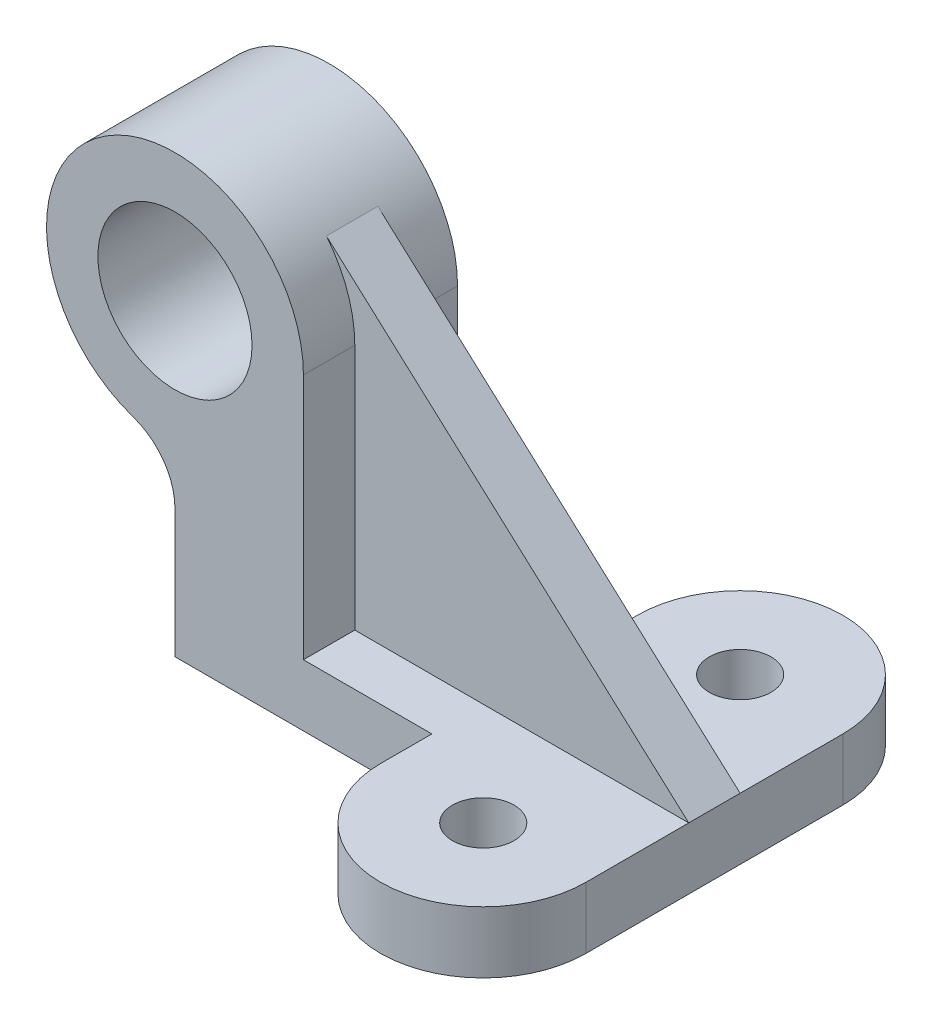
SolidWorks part; units mm, degrees
ref_plane "Front Plane" through (0, 0, 0) normal (0, 0, 1) x (1, 0, 0)
ref_plane "Top Plane" through (0, 0, 0) normal (0, 1, 0) x (1, 0, 0)
ref_plane "Right Plane" through (0, 0, 0) normal (1, 0, 0) x (0, 0, -1)
sketch "Sketch2" plane through (0, 0, 0) normal (0, 1, 0) x (1, 0, 0)
  line L0 (0, 150.8422) -> (0, -117.9442) construction
  line L1 (-243.4091, 0) -> (231.4014, 0) construction
  line L2 (0, -25) -> (0, 25) construction
  line L10 (20, -25) -> (20, 25)
  line L11 (-20, 25) -> (-20, 15)
  line L12 (-20, -25) -> (-20, -15)
  line L13 (-20, 15) -> (-70, 15)
  line L14 (-70, 15) -> (-70, -15)
  line L15 (-70, -15) -> (-20, -15)
  arc A4 (-20, -25) -> (20, -25) centre (0, -25) ccw
  arc A5 (20, 25) -> (-20, 25) centre (0, 25) ccw
  circle A6 centre (0, 25) radius 6
  circle A7 centre (0, -25) radius 6
  point P7 (0, 0)
extrude "Boss-Extrude1" add sketch "Sketch2" along normal blind 12
sketch "Sketch4" plane through (0, 0, 15) normal (0, 0, 1) x (1, 0, 0)
  line L0 (-70, 12) -> (-70, 25)
  line L1 (-45, 12) -> (-45, 60)
  line L2 (-70, 12) -> (-20, 12) construction
  arc A0 (-45, 60) -> (-78.1081, 36.3514) centre (-70, 60) ccw
  circle A1 centre (-70, 60) radius 15
  arc A2 (-70, 25) -> (-78.1081, 36.3514) centre (-82, 25) ccw
  line M5 (-20, 12) -> (-70, 12)
  dimension "D2" = 12
  dimension "D1" = 25
extrude "Boss-Extrude3" add sketch "Sketch4" against normal blind 30 contours L1 A0 L0 A1 M5
sketch "Sketch8" plane through (0, 0, 0) normal (0, 0, 1) x (1, 0, 0)
  line L0 (20, 12) -> (-50.5219, 75.6717)
  arc A0 (-45, 60) -> (-78.1081, 36.3514) centre (-70, 60) ccw construction
rib "Rib10" sketch "Sketch8" sketch "Sketch8" thickness 10 extrusion direction parallel to sketch draft on no parameters "D1"=10
